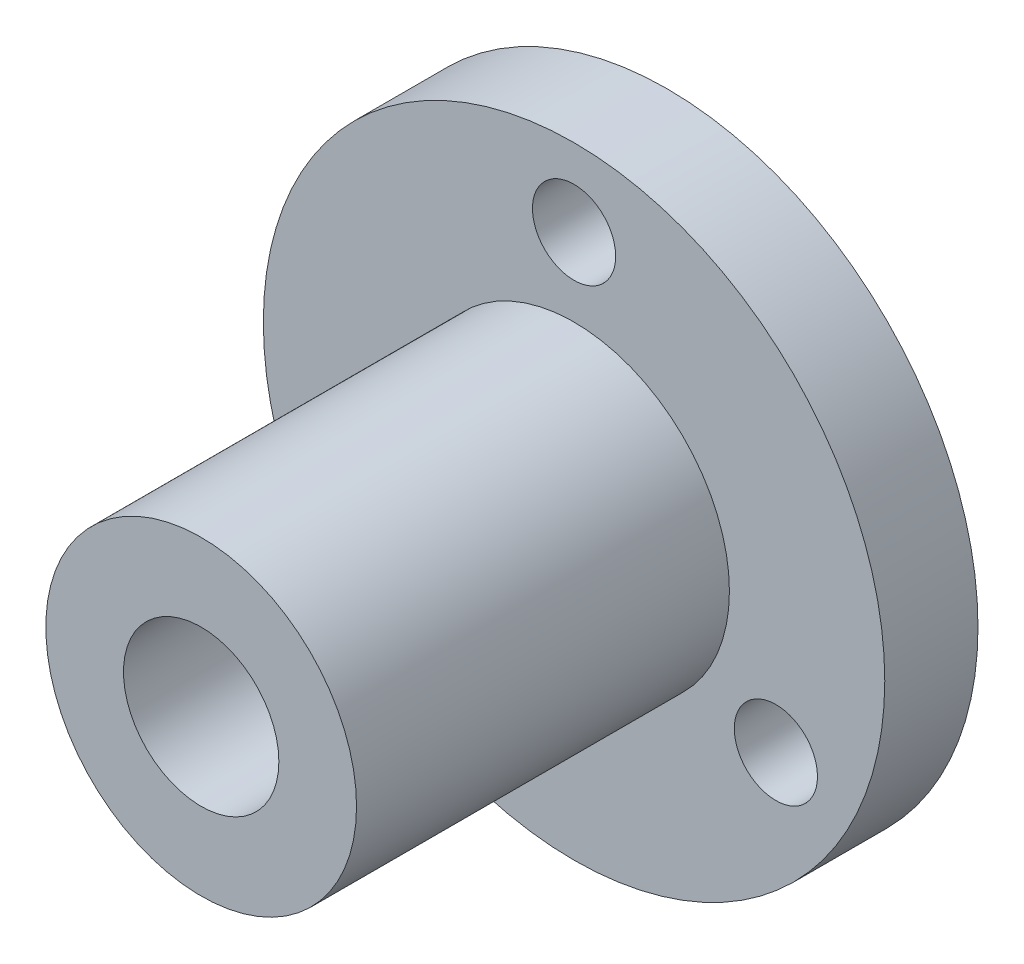
SolidWorks part; units mm, degrees
ref_plane "Piano frontale" through (0, 0, 0) normal (1, 0, 0) x (0, 1, 0)
ref_plane "Piano superiore" through (0, 0, 0) normal (0, 0, 1) x (0, 1, 0)
ref_plane "Piano destro" through (0, 0, 0) normal (0, 1, 0) x (-1, 0, 0)
sketch "Schizzo1" plane through (0, 0, 0) normal (0, 0, 1) x (0, 1, 0)
  circle A0 centre (0, 0) radius 12.7
  dimension "D1" = 25.4
extrude "Estrusione-Estrusione1" add sketch "Schizzo1" along normal blind 3.81
sketch "Schizzo2" plane through (0, 0, 3.81) normal (0, 0, 1) x (1, 0, 0)
  circle A0 centre (0, 0) radius 6.35
  dimension "D1" = 12.7
extrude "Estrusione-Estrusione2" add sketch "Schizzo2" along normal blind 15.24
hole_wizard "Fori Alesato Ø4.0mm1" positions "Schizzo5" profile "Schizzo6" hole size "Ø4.0" standard "ISO" end condition through all
sketch "Schizzo5" plane through (0, 0, 19.05) normal (0, 0, 1) x (1, 0, 0)
  point P0 (0, 0)
sketch "Schizzo6" plane through (0, 0, 19.05) normal (1, 0, 0) x (0, -1, 0)
  line L0 (0, 0) -> (0, 19.05)
  line L1 (0, 19.05) -> (3.175, 19.05)
  line L2 (3.175, 19.05) -> (3.175, 0)
  line L5 (3.175, 0) -> (0, 0)
  line L11 (0, -6.35) -> (0, 107.95) construction
  dimension "Thru Hole Dia." = 6.35
  dimension "Thru Hole Depth" = 19.05
hole_wizard "Foro per Vite M3-1" positions "Schizzo7" profile "Schizzo8" hole size "M3" standard "ISO" end condition through all
sketch "Schizzo7" plane through (0, 0, 3.81) normal (0, 0, 1) x (1, 0, 0)
  point P0 (0, 9.525)
  dimension "D1" = 9.525
sketch "Schizzo8" plane through (0, 9.525, 3.81) normal (1, 0, 0) x (0, -1, 0)
  line L0 (0, 0) -> (0, 3.81)
  line L1 (0, 3.81) -> (1.7, 3.81)
  line L2 (1.7, 3.81) -> (1.7, 0)
  line L5 (1.7, 0) -> (0, 0)
  line L11 (0, -6.35) -> (0, 107.95) construction
  dimension "Thru Hole Dia." = 3.4
  dimension "Thru Hole Depth" = 3.81
pattern_circular "RipetizioneCircolare2" count 3 over 360 about axis through (0, 0, 0) along (0, 0, 1) of "Foro per Vite M3-1"
